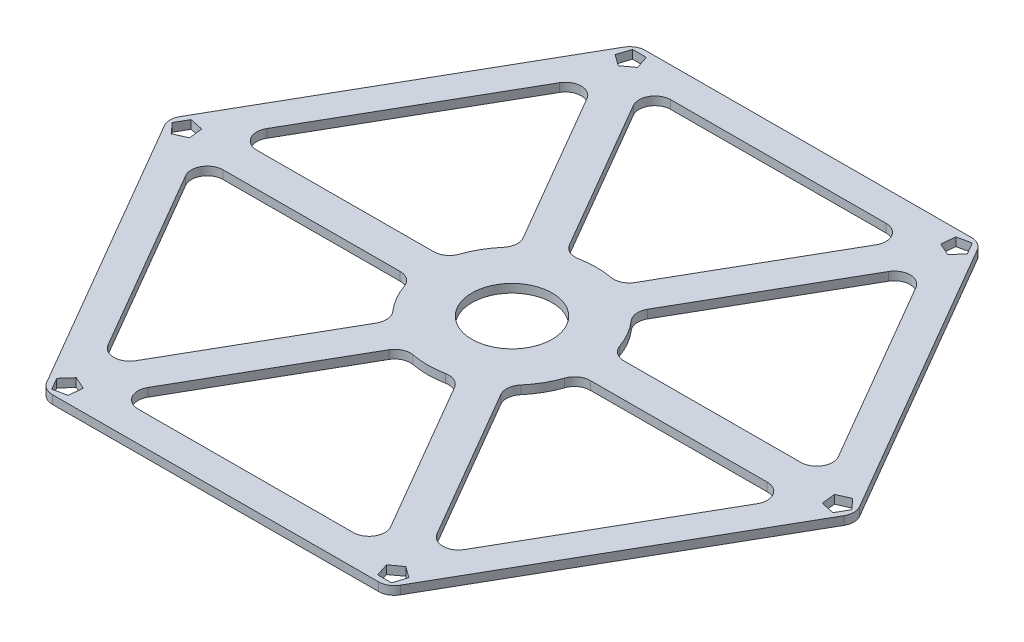
SolidWorks part; units mm, degrees
ref_plane "Front Plane" through (0, 0, 0) normal (0, 0, 1) x (1, 0, 0)
ref_plane "Top Plane" through (0, 0, 0) normal (0, 1, 0) x (1, 0, 0)
ref_plane "Right Plane" through (0, 0, 0) normal (1, 0, 0) x (0, 0, -1)
sketch "Sketch1" plane through (0, 0, 0) normal (0, 1, 0) x (1, 0, 0)
  line L0 (-31.0118, 53.34) -> (-30.9795, 42.6969) construction
  line L1 (-32.6705, 56.1929) -> (-64.9997, -0.197)
  line L2 (-64.9997, -0.197) -> (-32.3292, -56.3899)
  line L3 (-32.3292, -56.3899) -> (32.6705, -56.1929)
  line L4 (32.6705, -56.1929) -> (64.9997, 0.197)
  line L5 (64.9997, 0.197) -> (32.3292, 56.3899)
  line L6 (32.3292, 56.3899) -> (-32.6705, 56.1929)
  line L7 (-31.1934, 47.2773) -> (-56.5594, 3.0329)
  line L8 (-56.54, -3.3757) -> (-30.9063, -47.4655)
  line L9 (-25.3466, -50.6529) -> (25.6532, -50.4984)
  line L10 (31.1934, -47.2773) -> (56.5594, -3.0329)
  line L11 (56.54, 3.3757) -> (30.9063, 47.4655)
  line L12 (25.3466, 50.6529) -> (-25.6532, 50.4984)
  line L13 (-31.0118, 53.34) -> (-61.6997, -0.187) construction
  line L14 (-61.6997, -0.187) -> (-30.6879, -53.527) construction
  line L15 (-30.6879, -53.527) -> (31.0118, -53.34) construction
  line L16 (31.0118, -53.34) -> (61.6997, 0.187) construction
  line L17 (61.6997, 0.187) -> (30.6879, 53.527) construction
  line L18 (30.6879, 53.527) -> (-31.0118, 53.34) construction
  line L50 (28.7645, 52.4087) -> (31.1571, 51.3521)
  line L51 (-31.0051, 51.1151) -> (-28.8937, 52.6589)
  line L52 (-28.8937, 52.6589) -> (-29.7095, 55.144)
  line L58 (-31.1934, 47.2773) -> (-10.6492, 11.9413)
  line L60 (25.3466, 50.6529) -> (5.0169, 15.1931)
  line L66 (56.54, 3.3757) -> (15.6661, 3.2518)
  line L72 (31.1934, -47.2773) -> (10.6492, -11.9413)
  line L78 (-25.3466, -50.6529) -> (-5.0169, -15.1931)
  line L84 (-56.54, -3.3757) -> (-15.6661, -3.2518)
  line L89 (-5.1089, 15.1624) -> (-25.6532, 50.4984)
  line L91 (-29.7095, 55.144) -> (-32.325, 55.136)
  line L92 (10.5766, 12.0056) -> (30.9063, 47.4655)
  line L94 (-32.325, 55.136) -> (-33.1257, 52.6461)
  line L95 (15.6855, -3.1568) -> (56.5594, -3.0329)
  line L97 (-33.1257, 52.6461) -> (-31.0051, 51.1151)
  line L98 (5.1089, -15.1624) -> (25.6532, -50.4984)
  line L100 (31.1571, 51.3521) -> (32.9013, 53.3012)
  line L101 (-10.5766, -12.0056) -> (-30.9063, -47.4655)
  line L103 (32.9013, 53.3012) -> (31.5867, 55.5623)
  line L104 (-15.6855, 3.1568) -> (-56.5594, 3.0329)
  line L106 (31.5867, 55.5623) -> (29.03, 55.0108)
  line L107 (29.03, 55.0108) -> (28.7645, 52.4087)
  line L108 (59.7695, 1.2936) -> (60.0508, -1.3068)
  line L109 (60.0508, -1.3068) -> (62.6108, -1.8428)
  line L110 (62.6108, -1.8428) -> (63.9117, 0.4263)
  line L111 (63.9117, 0.4263) -> (62.1557, 2.3647)
  line L112 (62.1557, 2.3647) -> (59.7695, 1.2936)
  line L113 (31.0051, -51.1151) -> (28.8937, -52.6589)
  line L114 (28.8937, -52.6589) -> (29.7095, -55.144)
  line L115 (29.7095, -55.144) -> (32.325, -55.136)
  line L116 (32.325, -55.136) -> (33.1257, -52.6461)
  line L117 (33.1257, -52.6461) -> (31.0051, -51.1151)
  line L118 (-28.7645, -52.4087) -> (-31.1571, -51.3521)
  line L119 (-31.1571, -51.3521) -> (-32.9013, -53.3012)
  line L120 (-32.9013, -53.3012) -> (-31.5867, -55.5623)
  line L121 (-31.5867, -55.5623) -> (-29.03, -55.0108)
  line L122 (-29.03, -55.0108) -> (-28.7645, -52.4087)
  line L123 (-59.7695, -1.2936) -> (-60.0508, 1.3068)
  line L124 (-60.0508, 1.3068) -> (-62.6108, 1.8428)
  line L125 (-62.6108, 1.8428) -> (-63.9117, -0.4263)
  line L126 (-63.9117, -0.4263) -> (-62.1557, -2.3647)
  line L127 (-62.1557, -2.3647) -> (-59.7695, -1.2936)
  circle A0 centre (0, 0) radius 56.2917 construction
  circle A1 centre (0, 0) radius 50.5759 construction
  circle A2 centre (0, 0) radius 53.4338 construction
  circle A3 centre (-31.0118, 53.34) radius 1.8 construction
  arc A4 (-10.6492, 11.9413) -> (-15.6855, 3.1568) centre (0, 0) ccw
  arc A5 (5.0169, 15.1931) -> (-5.1089, 15.1624) centre (0, 0) ccw
  arc A6 (15.6661, 3.2518) -> (10.5766, 12.0056) centre (0, 0) ccw
  arc A7 (10.6492, -11.9413) -> (15.6855, -3.1568) centre (0, 0) ccw
  arc A8 (-5.0169, -15.1931) -> (5.1089, -15.1624) centre (0, 0) ccw
  arc A9 (-15.6661, -3.2518) -> (-10.5766, -12.0056) centre (0, 0) ccw
  point P53 (0, 0)
  point P58 (-0.0078, -0.0152)
  point P87 (0, 0)
  dimension "D1" = 65
  dimension "D2" = 30
  dimension "D3" = 3.3
  dimension "D4" = 6
  dimension "D7" = 6
extrude "Boss-Extrude1" add sketch "Sketch1" along normal blind 1.6
fillet "Fillet1" radius 3 6 edges at (-64.9997, 0.8, 0.197) (-32.3292, 0.8, 56.3899) (32.6705, 0.8, 56.1929) (64.9997, 0.8, -0.197) (32.3292, 0.8, -56.3899) (-32.6705, 0.8, -56.1929)
sketch "Sketch2" plane through (0, 0, 0) normal (0, 1, 0) x (1, 0, 0)
fillet "Fillet2" radius 3 24 edges at (-25.3466, 0.8, 50.6529) (31.1934, 0.8, 47.2773) (25.6532, 0.8, 50.4984) (-30.9063, 0.8, 47.4655) (-56.54, 0.8, 3.3757) (-15.6661, 0.8, 3.2518) (-10.5766, 0.8, 12.0056) (-31.1934, 0.8, -47.2773) (-56.5594, 0.8, -3.0329) (-15.6855, 0.8, -3.1568) (-10.6492, 0.8, -11.9413) (-25.6532, 0.8, -50.4984) (25.3466, 0.8, -50.6529) (56.54, 0.8, -3.3757) (56.5594, 0.8, 3.0329) (30.9063, 0.8, -47.4655) (-5.0169, 0.8, 15.1931) (5.1089, 0.8, 15.1624) (10.6492, 0.8, 11.9413) (15.6855, 0.8, 3.1568) (15.6661, 0.8, -3.2518) (10.5766, 0.8, -12.0056) (5.0169, 0.8, -15.1931) (-5.1089, 0.8, -15.1624)
ref_plane "Plane1" through (0, 3.6, 0) normal (0, 1, 0) x (1, 0, 0)
sketch "Sketch3" plane through (0, 3.6, 0) normal (0, 1, 0) x (1, 0, 0)
  circle A0 centre (0, 0) radius 7.6
extrude "Cut-Extrude1" cut sketch "Sketch3" against normal blind 10
scale "Scale1" scale about centroid uniform scaling yes scale factor 1.15
